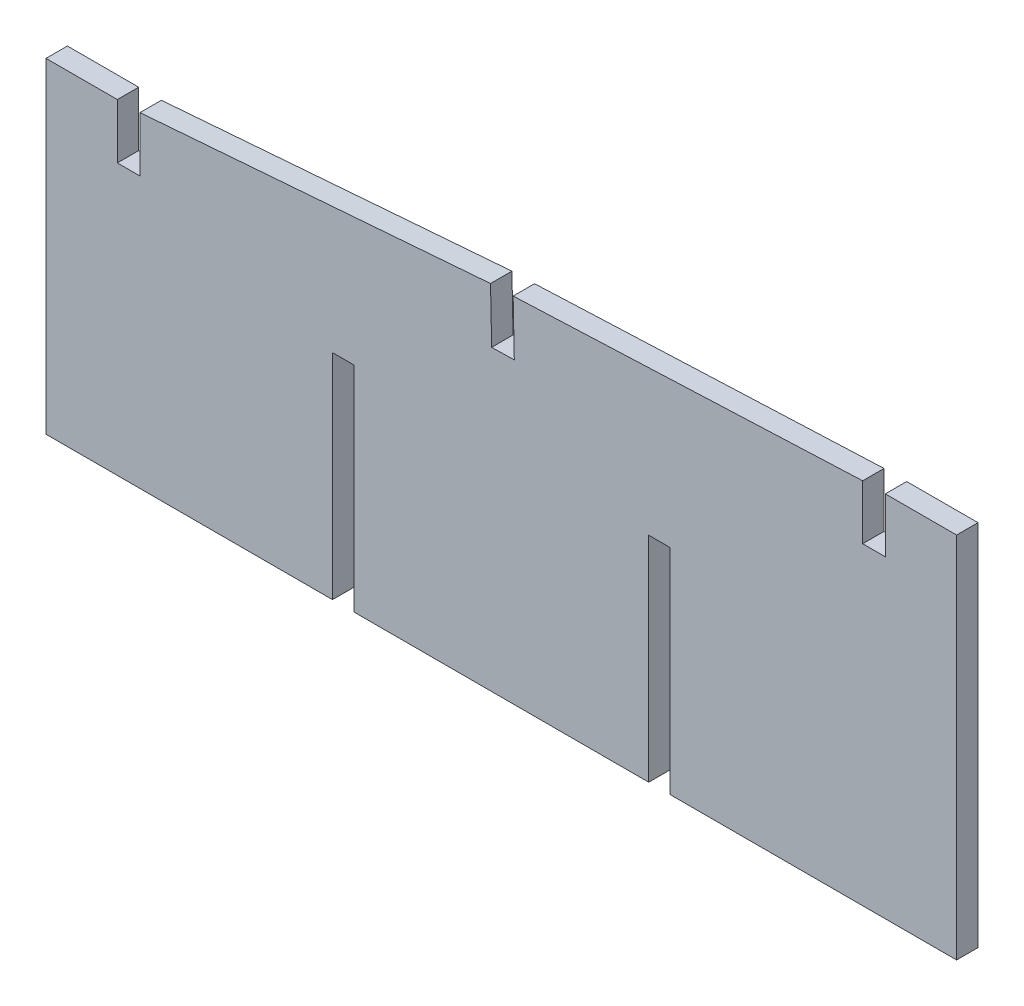
SolidWorks part; units mm, degrees
ref_plane "Front Plane" through (0, 0, 0) normal (0, 0, 1) x (1, 0, 0)
ref_plane "Top Plane" through (0, 0, 0) normal (0, 1, 0) x (1, 0, 0)
ref_plane "Right Plane" through (0, 0, 0) normal (1, 0, 0) x (0, 0, -1)
ref_plane "Plane1" through (0, 0, -420) normal (0, 0, 1) x (1, 0, 0)
sketch "Sketch2" plane through (0, 0, -420) normal (0, 0, 1) x (1, 0, 0)
  line L0 (374.396, 60.4053) -> (374.396, 68.0485)
  line L1 (371.221, 60.4053) -> (371.221, 68.0485)
  line L2 (371.221, 60.4053) -> (374.396, 60.4053)
  line L3 (374.396, 68.0485) -> (371.221, 68.0485)
  line L5 (371.221, 60.4053) -> (374.396, 60.4053)
  line L6 (371.221, 60.4053) -> (371.221, 68.0485)
  line L7 (374.396, 60.4053) -> (374.396, 68.0485)
  line L8 (266.7, 62.0886) -> (266.7, 54.3898)
  line L9 (269.875, 62.0886) -> (269.875, 54.3898)
  line L10 (266.7, 62.0886) -> (269.875, 62.0886)
  line L11 (266.7, 54.3898) -> (269.875, 54.3898)
  line L12 (266.7, 54.3898) -> (269.875, 54.3898)
  line L14 (269.875, 62.0886) -> (269.875, 54.3898)
  line L15 (266.7, 62.0886) -> (266.7, 54.3898)
  line L16 (322.2098, 65.98) -> (322.3689, 58.306)
  line L17 (319.0355, 65.9145) -> (319.1945, 58.2405)
  line L18 (319.1945, 58.2405) -> (322.3689, 58.306)
  line L19 (322.2098, 65.98) -> (319.0355, 65.9145)
  line L21 (319.1945, 58.2405) -> (322.3689, 58.306)
  line L22 (319.0355, 65.9145) -> (319.1945, 58.2405)
  line L23 (322.2098, 65.98) -> (322.3689, 58.306)
  line L24 (371.221, 68.0485) -> (322.2098, 65.98)
  line L25 (319.0355, 65.9145) -> (269.875, 62.0886)
  line L26 (266.7, 62.0886) -> (256.7, 62.0886)
  line L27 (256.7, 62.0886) -> (256.7, 16.4388)
  line L28 (256.7, 16.4388) -> (296.875, 16.4388)
  line L29 (384.396, 16.4388) -> (384.396, 68.0485)
  line L30 (384.396, 68.0485) -> (374.396, 68.0485)
  line L31 (344.221, 46.4388) -> (344.221, 16.4388) construction
  line L32 (341.221, 16.4388) -> (341.221, 46.4388) construction
  line L33 (341.221, 46.4388) -> (344.221, 46.4388) construction
  line L34 (299.875, 46.4388) -> (299.875, 16.4388) construction
  line L35 (296.875, 46.4388) -> (299.875, 46.4388) construction
  line L36 (296.875, 16.4388) -> (296.875, 46.4388) construction
  line L37 (344.221, 46.4388) -> (344.221, 16.4388)
  line L38 (341.221, 16.4388) -> (341.221, 46.4388)
  line L39 (341.221, 46.4388) -> (344.221, 46.4388)
  line L40 (299.875, 46.4388) -> (299.875, 16.4388)
  line L41 (296.875, 46.4388) -> (299.875, 46.4388)
  line L42 (296.875, 16.4388) -> (296.875, 46.4388)
  line L43 (299.875, 16.4388) -> (341.221, 16.4388)
  line L44 (344.221, 16.4388) -> (384.396, 16.4388)
  dimension "D1" = 10
  dimension "D2" = 10
extrude "Boss-Extrude1" add sketch "Sketch2" against normal blind 3
